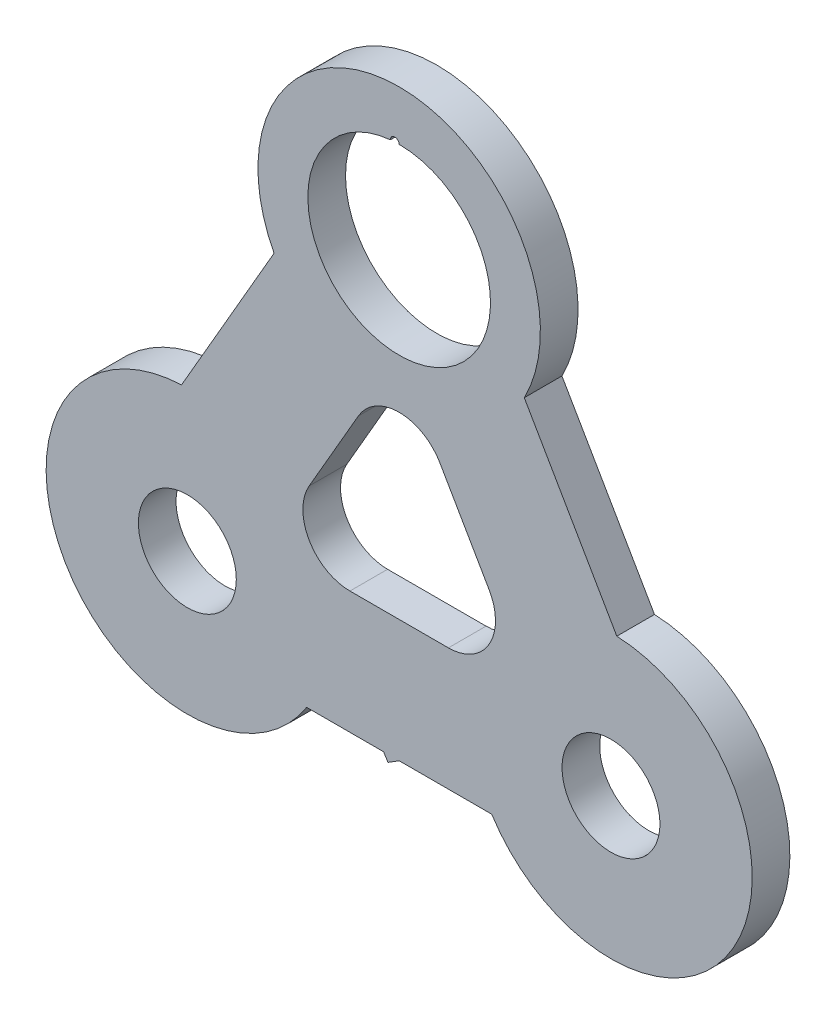
SolidWorks part; units mm, degrees
ref_plane "前视基准面" through (0, 0, 0) normal (0, 0, 1) x (1, 0, 0)
ref_plane "上视基准面" through (0, 0, 0) normal (0, 1, 0) x (1, 0, 0)
ref_plane "右视基准面" through (0, 0, 0) normal (1, 0, 0) x (0, 0, -1)
sketch "草图1" plane through (0, 0, 0) normal (0, 0, 1) x (1, 0, 0)
  line L0 (-18.4946, 4.743) -> (-23.4095, -3.7697)
  line L1 (-18.4946, 4.743) -> (-13.5798, 13.2557)
  line L2 (-0.2914, -26.7859) -> (9.5382, -26.7859)
  line L3 (-0.2914, -26.7859) -> (-10.1211, -26.7859) construction
  line L4 (17.9118, 4.743) -> (12.9969, 13.2557)
  line L5 (17.9118, 4.743) -> (22.8266, -3.7697)
  line L6 (9.2682, -6.2859) -> (4.0387, 2.7719)
  line L7 (-4.6216, 2.7719) -> (-9.851, -6.2859)
  line L8 (4.938, -13.7859) -> (-5.5209, -13.7859)
  line L9 (-0.2914, 20.2141) -> (22.2086, -18.757) construction
  line L10 (-0.2914, 20.2141) -> (-22.7914, -18.757) construction
  line L11 (-22.7914, -18.757) -> (22.2086, -18.757) construction
  line L12 (-0.2914, -26.7859) -> (-1.4798, -27.5312)
  line L13 (-1.4798, -27.5312) -> (-1.9473, -26.7859)
  line L14 (-1.9473, -26.7859) -> (-10.1211, -26.7859)
  circle A0 centre (-0.2914, 20.2141) radius 5.2
  circle A1 centre (22.2086, -18.757) radius 5.2
  circle A2 centre (-22.7914, -18.757) radius 5.2
  circle A3 centre (-0.2914, 0.2719) radius 5 construction
  circle A4 centre (4.938, -8.7859) radius 5 construction
  circle A5 centre (-5.5209, -8.7859) radius 5 construction
  circle A6 centre (-0.2914, 20.2141) radius 15 construction
  circle A7 centre (22.2086, -18.757) radius 15 construction
  circle A8 centre (-22.7914, -18.757) radius 15 construction
  arc A9 (12.9969, 13.2557) -> (-13.5798, 13.2557) centre (-0.2914, 20.2141) ccw
  arc A10 (22.8266, -3.7697) -> (9.5382, -26.7859) centre (22.2086, -18.757) cw
  arc A11 (-10.1211, -26.7859) -> (-23.4095, -3.7697) centre (-22.7914, -18.757) cw
  arc A12 (-5.5209, -13.7859) -> (-9.851, -6.2859) centre (-5.5209, -8.7859) cw
  arc A13 (4.938, -13.7859) -> (9.2682, -6.2859) centre (4.938, -8.7859) ccw
  arc A14 (4.0387, 2.7719) -> (-4.6216, 2.7719) centre (-0.2914, 0.2719) ccw
  dimension "D1" = 45
  dimension "D2" = 10.4
extrude "凸台-拉伸1" add sketch "草图1" along normal blind 4
sketch "草图2" plane through (0, 0, 4) normal (0, 0, 1) x (1, 0, 0)
  circle A0 centre (-0.2914, 20.2141) radius 9.7 construction
  arc A1 (-0.2914, 29.9141) -> (-1.2178, 29.8698) centre (-0.7546, 29.892) ccw
  arc A2 (-1.2178, 29.8698) -> (-0.2914, 29.9141) centre (-0.2914, 20.2141) ccw
  dimension "D1" = 19.4
extrude "切除-拉伸1" cut sketch "草图2" against normal blind 4 contours A2 A1
